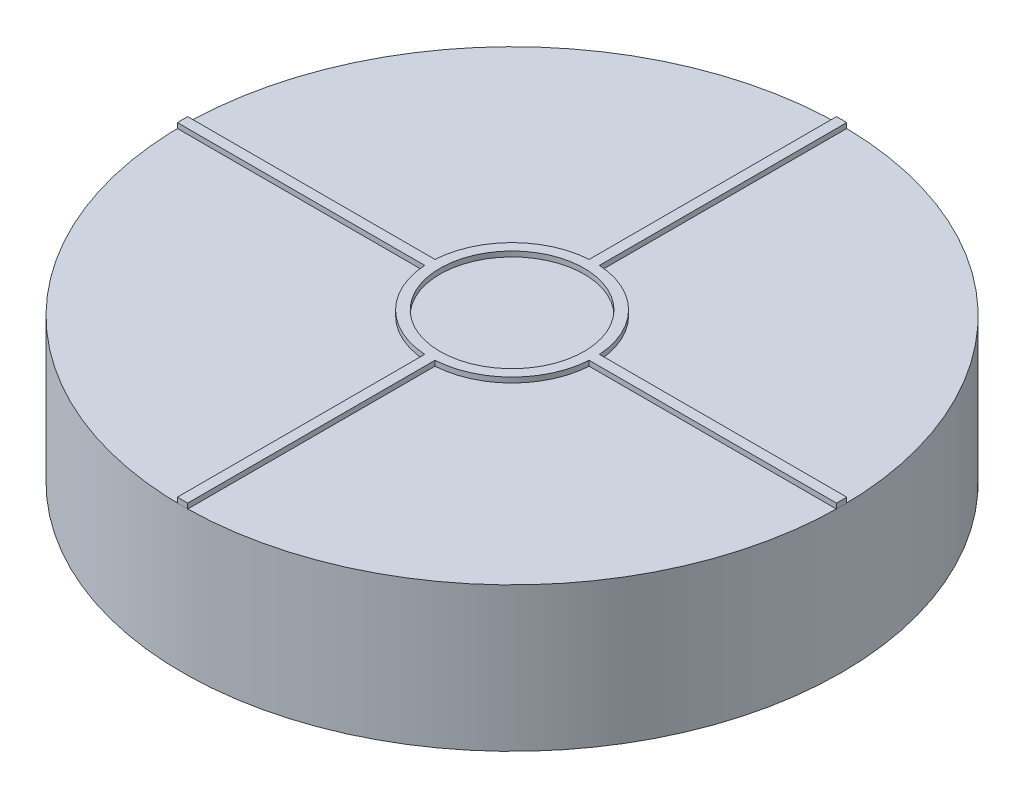
SolidWorks part; units mm, degrees
ref_plane "Front Plane" through (0, 0, 0) normal (0, 0, 1) x (1, 0, 0)
ref_plane "Top Plane" through (0, 0, 0) normal (0, 1, 0) x (1, 0, 0)
ref_plane "Right Plane" through (0, 0, 0) normal (1, 0, 0) x (0, 0, -1)
sketch "Sketch2" plane through (0, 0, 0) normal (0, 0, 1) x (1, 0, 0)
  line L0 (0, 0) -> (0, 7) construction
  line L1 (0, 0) -> (-16, 0)
  line L2 (-16, 0) -> (-16, 7)
  line L3 (-16, 7) -> (0, 7)
  line L4 (0, 7) -> (0, 6)
  line L5 (0, 6) -> (-15, 6)
  line L6 (-15, 6) -> (-15, 1)
  line L7 (-15, 1) -> (0, 1)
  line L8 (0, 1) -> (0, 0)
  point P7 (-16, 3.5)
  dimension "D1" = 16
  dimension "D2" = 1
  dimension "D3" = 1
  dimension "D4" = 1
  dimension "D5" = 7
revolve "Revolve1" add sketch "Sketch2" angle 360 about L0
sketch "Sketch3" plane through (0, 1, 0) normal (0, 1, 0) x (1, 0, 0)
  circle A0 centre (0, 0) radius 15 construction
  circle A1 centre (0, 0) radius 15
extrude "Boss-Extrude1" add sketch "Sketch3" along normal blind 4 separate body
sketch "Sketch4" plane through (0, 7, 0) normal (0, 1, 0) x (1, 0, 0)
  line L0 (-16, 0) -> (-4, 0) construction
  line L1 (-16, -0.25) -> (-3.9922, -0.25)
  line L2 (-16, 0.25) -> (-3.9922, 0.25)
  line L3 (0, -16) -> (0, -4) construction
  line L4 (0.25, -16) -> (0.25, -3.9922)
  line L5 (-0.25, -16) -> (-0.25, -3.9922)
  line L6 (0.25, 3.9922) -> (0.25, 16)
  line L7 (0.25, -16) -> (0.25, 16) construction
  line L8 (0, 4) -> (0, 16) construction
  line L9 (0, -16) -> (0, 16) construction
  line L10 (-0.25, 3.9922) -> (-0.25, 16)
  line L11 (-0.25, -16) -> (-0.25, 16) construction
  line L12 (-0.25, 0.25) -> (0.25, 0.25)
  line L13 (-16, 0.25) -> (16, 0.25) construction
  line L14 (-0.25, 0) -> (0.25, 0) construction
  line L15 (-16, 0) -> (16, 0) construction
  line L16 (-0.25, -0.25) -> (0.25, -0.25)
  line L17 (-16, -0.25) -> (16, -0.25) construction
  line L18 (-0.25, -0.25) -> (-0.25, 0.25)
  line L19 (0, -0.25) -> (0, 0.25) construction
  line L20 (0.25, -0.25) -> (0.25, 0.25)
  line L21 (3.9922, -0.25) -> (16, -0.25)
  line L22 (4, 0) -> (16, 0) construction
  line L23 (3.9922, 0.25) -> (16, 0.25)
  circle A0 centre (0, 0) radius 4
  circle A1 centre (0, 0) radius 3.5
  circle A2 centre (0, 0) radius 16 construction
  circle M5 centre (0, 0) radius 16
  dimension "D1" = 7
  dimension "D2" = 8
  dimension "D3" = 0.25
  dimension "D4" = 0.25
  dimension "D5" = 0.25
  dimension "D6" = 0.25
extrude "Boss-Extrude2" add sketch "Sketch4" along normal blind 0.25 separate body contours A0 A1 | A0 L21 L23 M5 | A0 L6 L10 M5 | A0 L2 L1 M5 | A0 L5 L4 M5
sketch "Sketch5" plane through (0, 0, 0) normal (1, 0, 0) x (0, 0, -1)
  line L0 (0, 0) -> (0, 10.1099) construction
  line L1 (0, 7.5) -> (0, 1.5)
  arc A0 (0, 7.5) -> (0, 1.5) centre (0, 4.5) ccw
  dimension "D2" = 3
  dimension "D1" = 4.5
revolve "Cut-Revolve1" cut sketch "Sketch5" angle 360 about L1
